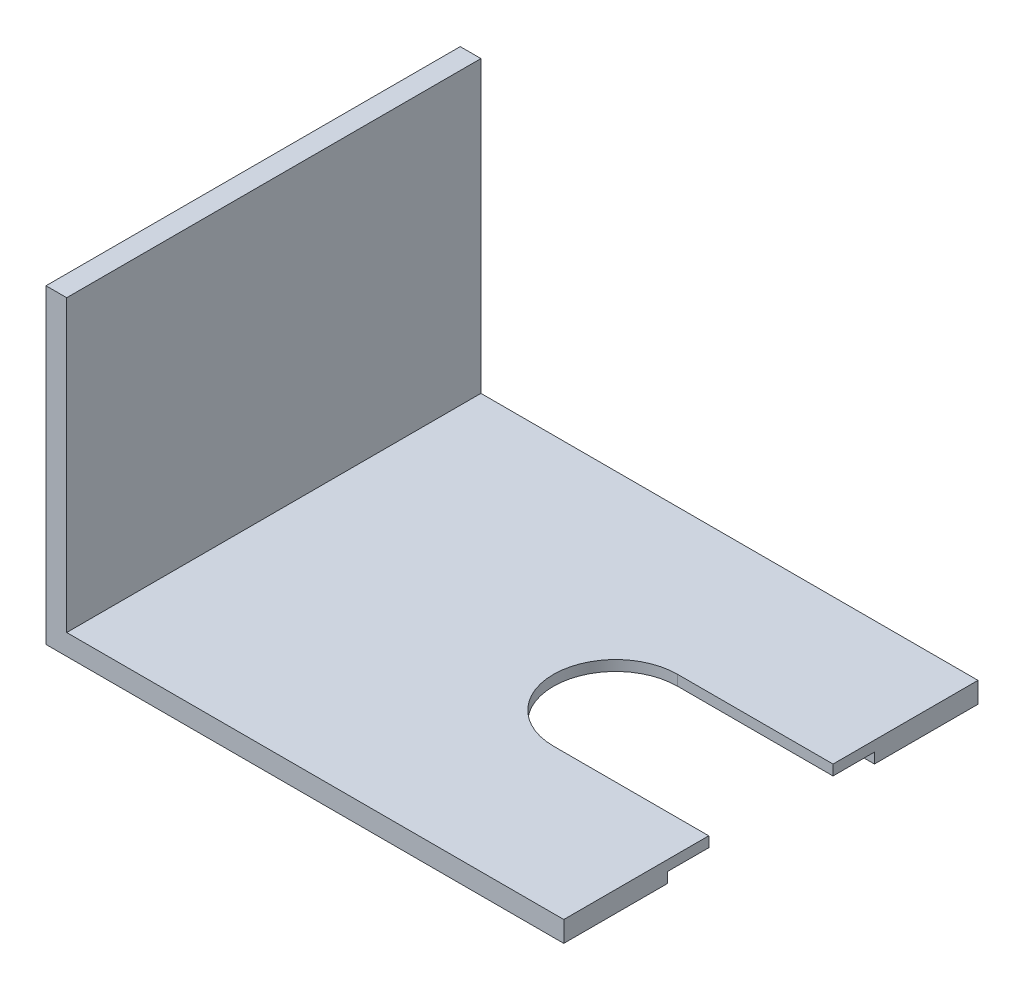
SolidWorks part; units mm, degrees
ref_plane "Front Plane" through (0, 0, 0) normal (0, 0, 1) x (1, 0, 0)
ref_plane "Top Plane" through (0, 0, 0) normal (0, 1, 0) x (1, 0, 0)
ref_plane "Right Plane" through (0, 0, 0) normal (1, 0, 0) x (0, 0, -1)
sketch "Sketch1" plane through (0, 0, 0) normal (0, 0, 1) x (1, 0, 0)
  line L0 (0, 0) -> (0, 30)
  line L1 (0, 30) -> (2, 30)
  line L2 (2, 30) -> (2, 2)
  line L3 (2, 2) -> (50, 2)
  line L4 (50, 2) -> (50, 0)
  line L5 (50, 0) -> (0, 0)
extrude "Boss-Extrude1" add sketch "Sketch1" along normal blind 40
sketch "Sketch4" plane through (0, 0, 0) normal (0, -1, 0) x (-1, 0, 0)
  line L0 (-35, -26) -> (-50, -26)
  line L1 (-50, -40) -> (-50, 0) construction
  line L2 (-35, -14) -> (-50, -14)
  circle A0 centre (-35, -20) radius 6
  line M2 (-50, 0) -> (-50, -40)
extrude "Cut-Extrude1" cut sketch "Sketch4" against normal through all contours A0 L2 L0 M2 | A0
sketch "Sketch5" plane through (0, 0, 0) normal (0, -1, 0) x (-1, 0, 0)
  line L0 (-35, -30) -> (-50, -30)
  line L1 (-50, -40) -> (-50, -26) construction
  line L2 (-50, -30) -> (-50, -10)
  line L3 (-50, -14) -> (-50, 0) construction
  line L4 (-50, -10) -> (-34.0279, -10.0474)
  circle A0 centre (-35, -20) radius 10
  line M1 (-35, -26) -> (-50, -26)
  line M2 (-50, -26) -> (-50, -40)
  line M6 (-50, 0) -> (-50, -14)
  line M7 (-50, -14) -> (-35, -14)
  arc M8 (-35, -14) -> (-35, -26) centre (-35, -20) cw
extrude "Cut-Extrude2" cut sketch "Sketch5" against normal blind 1 contours A0 L0 M1 M2 | A0 L4 M6 M7 | A0 L4 M1 M7 M8
